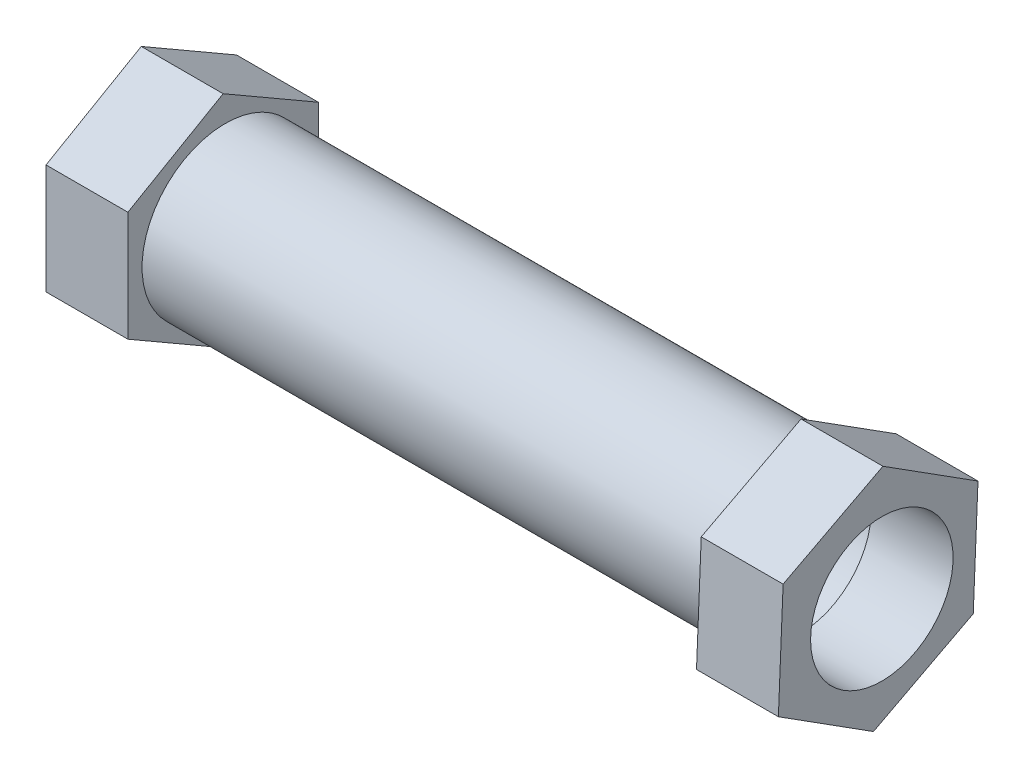
SolidWorks part; units mm, degrees
ref_plane "Front Plane" through (0, 0, 0) normal (0, 0, 1) x (1, 0, 0)
ref_plane "Top Plane" through (0, 0, 0) normal (0, 1, 0) x (1, 0, 0)
ref_plane "Right Plane" through (0, 0, 0) normal (1, 0, 0) x (0, 0, -1)
sketch "Sketch1" plane through (0, 0, 0) normal (1, 0, 0) x (0, 0, -1)
  circle A0 centre (1.2897, 0) radius 50.8004
  circle A1 centre (1.2897, 0) radius 47.813
extrude "Boss-Extrude2" add sketch "Sketch1" along normal blind 350
sketch "Sketch3" plane through (350, 0, 0) normal (1, 0, 0) x (0, 0, -1)
  line L1 (29.4119, -18.9904) -> (30.3159, 11.3837)
  line L2 (30.3159, 11.3837) -> (4.4631, 27.3538)
  line L3 (4.4631, 27.3538) -> (-22.2937, 12.9496)
  line L4 (-22.2937, 12.9496) -> (-23.1978, -17.4246)
  line L5 (-23.1978, -17.4246) -> (2.655, -33.3946)
  line L6 (2.655, -33.3946) -> (29.4119, -18.9904)
  line L7 (58.0556, -36.8554) -> (60.9455, 31.8499)
  line L8 (60.9455, 31.8499) -> (2.8899, 68.7054)
  line L9 (2.8899, 68.7054) -> (-58.0556, 36.8554)
  line L10 (-58.0556, 36.8554) -> (-60.9455, -31.8499)
  line L11 (-60.9455, -31.8499) -> (-2.8899, -68.7054)
  line L12 (-2.8899, -68.7054) -> (58.0556, -36.8554)
  circle A0 centre (3.5591, -3.0204) radius 26.3165 construction
  circle A1 centre (0, 0) radius 59.5532 construction
  point P9 (-38.2851, 22.8279)
extrude "Boss-Extrude5" add sketch "Sketch3" along normal blind 50
sketch "Sketch5" plane through (0, 0, 0) normal (-1, 0, 0) x (0, 0, 1)
  line L1 (0, -67.1614) -> (58.1634, -33.5807)
  line L2 (58.1634, -33.5807) -> (58.1634, 33.5807)
  line L3 (58.1634, 33.5807) -> (0, 67.1614)
  line L4 (0, 67.1614) -> (-58.1634, 33.5807)
  line L5 (-58.1634, 33.5807) -> (-58.1634, -33.5807)
  line L6 (-58.1634, -33.5807) -> (0, -67.1614)
  circle A0 centre (0, 0) radius 58.1634 construction
extrude "Boss-Extrude11" add sketch "Sketch5" along normal blind 50
sketch "Sketch6" plane through (0, 0, 0) normal (1, 0, 0) x (0, 0, -1)
  circle A0 centre (2.1673, 0) radius 44.9963
  point P2 (2.0814, 2.5081)
  point P3 (2.1673, 0)
extrude "Cut-Extrude2" cut sketch "Sketch6" against normal blind 50
sketch "Sketch7" plane through (350, 0, 0) normal (-1, 0, 0) x (0, 0, 1)
  circle A0 centre (-2.2315, -1.0944) radius 43.5179
  point P2 (-2.2315, -1.0944)
extrude "Cut-Extrude3" cut sketch "Sketch7" against normal blind 50
